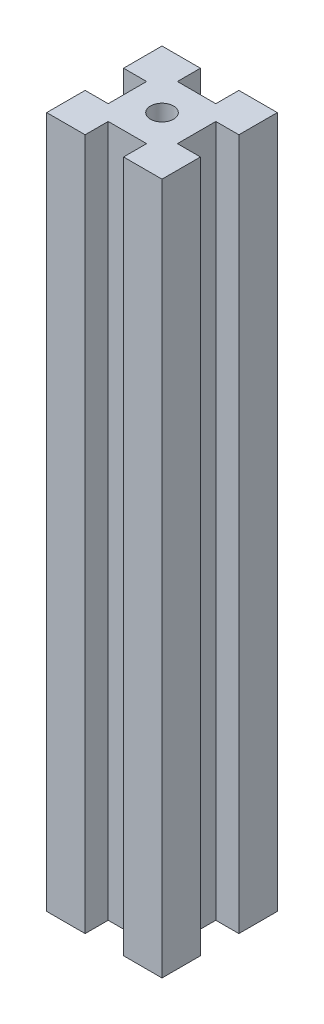
SolidWorks part; units mm, degrees
ref_plane "Front Plane" through (0, 0, 0) normal (0, 0, 1) x (1, 0, 0)
ref_plane "Top Plane" through (0, 0, 0) normal (0, 1, 0) x (1, 0, 0)
ref_plane "Right Plane" through (0, 0, 0) normal (1, 0, 0) x (0, 0, -1)
sketch "Sketch1" plane through (0, 0, 0) normal (0, 1, 0) x (1, 0, 0)
  line L0 (0, 0) -> (0, 79.4291) construction
  line L1 (0, -55) -> (0, 55) construction
  line L2 (0, 0) -> (123.1571, 0) construction
  line L3 (2.5, 4.5) -> (-2.5, 4.5)
  line L4 (-2.5, 4.5) -> (-2.5, 7.5)
  line L5 (-2.5, 7.5) -> (-7.5, 7.5)
  line L6 (-7.5, 7.5) -> (-7.5, 2.5)
  line L8 (-7.5, 2.5) -> (-4.5, 2.5)
  line L9 (-4.5, 2.5) -> (-4.5, -2.5)
  line L11 (-55, 0) -> (55, 0) construction
  line L12 (7.5, 2.5) -> (4.5, 2.5)
  line L13 (4.5, 2.5) -> (4.5, -2.5)
  line L14 (7.5, 7.5) -> (7.5, 2.5)
  line L15 (2.5, 7.5) -> (7.5, 7.5)
  line L16 (2.5, 4.5) -> (2.5, 7.5)
  line L17 (2.5, -4.5) -> (2.5, -7.5)
  line L18 (2.5, -7.5) -> (7.5, -7.5)
  line L19 (7.5, -7.5) -> (7.5, -2.5)
  line L20 (7.5, -2.5) -> (4.5, -2.5)
  line L21 (-7.5, -2.5) -> (-4.5, -2.5)
  line L22 (-7.5, -7.5) -> (-7.5, -2.5)
  line L23 (-2.5, -7.5) -> (-7.5, -7.5)
  line L24 (-2.5, -4.5) -> (-2.5, -7.5)
  line L25 (2.5, -4.5) -> (-2.5, -4.5)
  circle A0 centre (0, 0) radius 1.5
  point P21 (0, 4.5)
  point P26 (4.5, 0)
  point P27 (-4.5, 0)
  point P31 (0, -4.5)
  dimension "D7" = 3
  dimension "D1" = 5
  dimension "D2" = 3
  dimension "D3" = 5
  dimension "D4" = 2.5
  dimension "D5" = 3
  dimension "D6" = 2.5
extrude "Boss-Extrude1" add sketch "Sketch1" along normal blind 90
